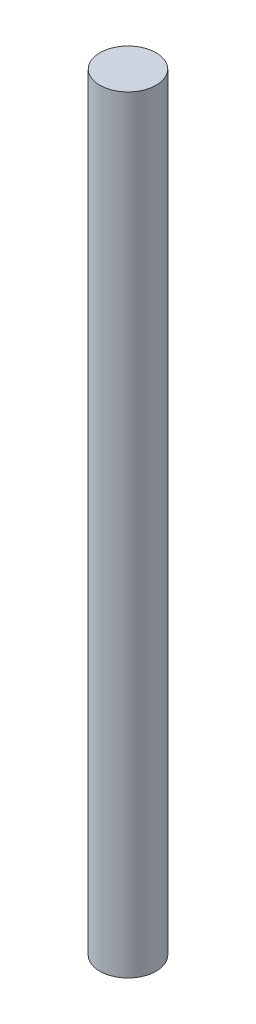
SolidWorks part; units mm, degrees
ref_plane "Front Plane" through (0, 0, 0) normal (0, 0, 1) x (1, 0, 0)
ref_plane "Top Plane" through (0, 0, 0) normal (0, 1, 0) x (1, 0, 0)
ref_plane "Right Plane" through (0, 0, 0) normal (1, 0, 0) x (0, 0, -1)
sketch "Sketch1" plane through (0, 0, 0) normal (0, 1, 0) x (1, 0, 0)
  circle A0 centre (0, 0) radius 11
  dimension "D1" = 22
extrude "Boss-Extrude1" add sketch "Sketch1" along normal blind 300
